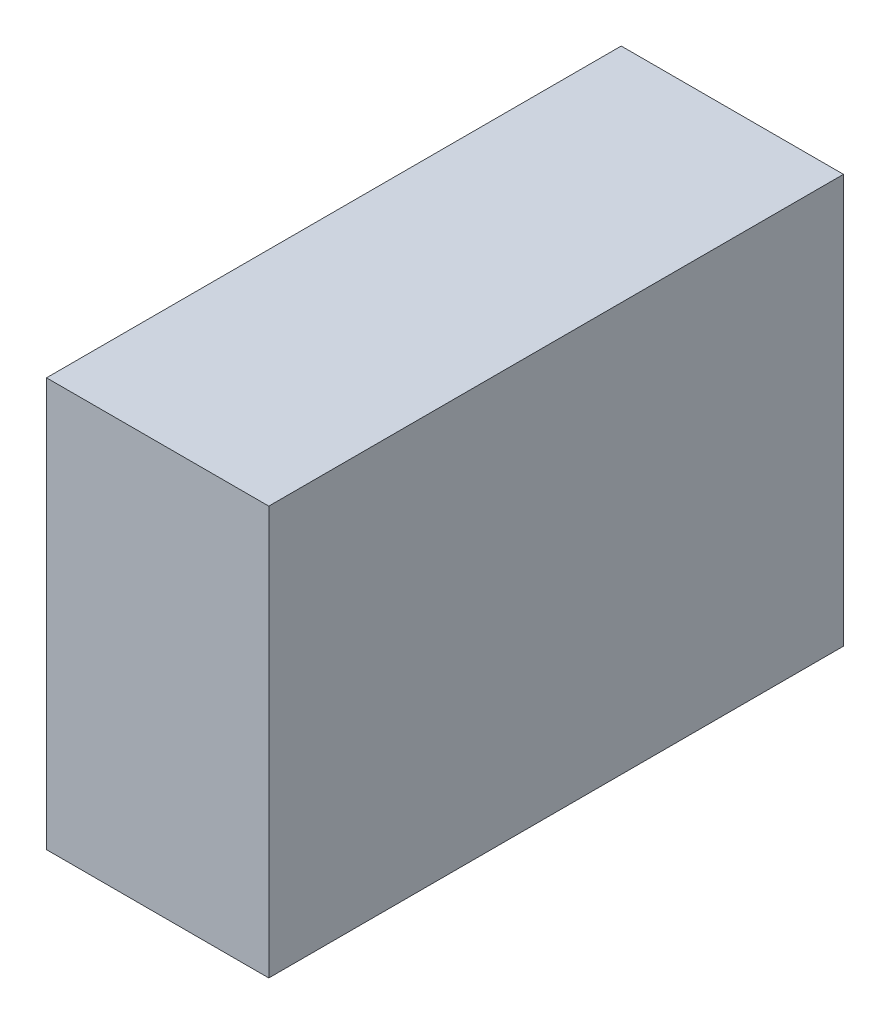
SolidWorks part; units mm, degrees
ref_plane "Front Plane" through (0, 0, 0) normal (0, 0, 1) x (1, 0, 0)
ref_plane "Top Plane" through (0, 0, 0) normal (0, 1, 0) x (1, 0, 0)
ref_plane "Right Plane" through (0, 0, 0) normal (1, 0, 0) x (0, 0, -1)
other "Graphic1"
other "Graphic (Closed) -1"
sketch "Sketch2" plane through (0, 0, 0) normal (1, 0, 0) x (0, 0, -1)
  line L1 (371.3884, 67.8837) -> (305.7122, 67.8837)
  line L2 (371.3884, 67.8837) -> (371.3884, 114.5867)
  line L3 (371.3884, 114.5867) -> (305.7122, 114.5867)
  line L4 (305.7122, 67.8837) -> (305.7122, 114.5867)
extrude "Boss-Extrude1" add sketch "Sketch2" along normal mid plane 25.4
